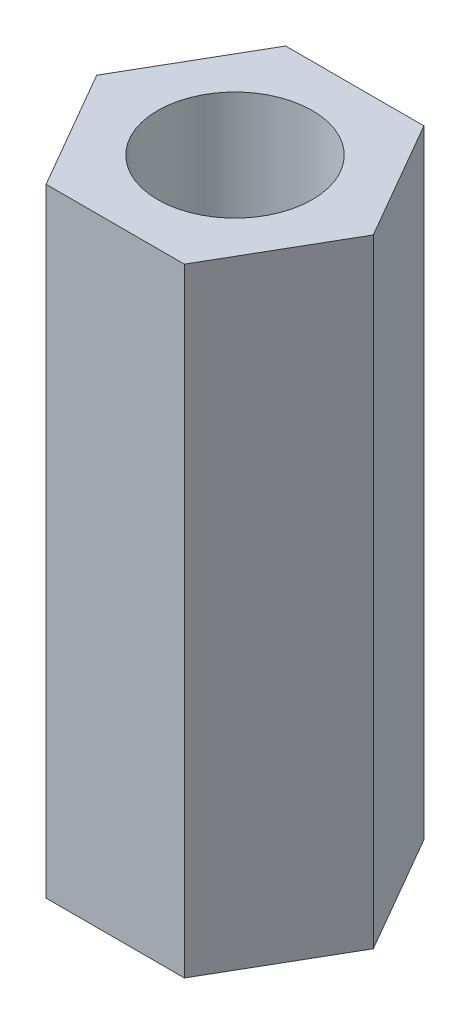
SolidWorks part; units mm, degrees
ref_plane "前视基准面" through (0, 0, 0) normal (0, 0, 1) x (1, 0, 0)
ref_plane "上视基准面" through (0, 0, 0) normal (0, 1, 0) x (1, 0, 0)
ref_plane "右视基准面" through (0, 0, 0) normal (1, 0, 0) x (0, 0, -1)
sketch "草图1" plane through (0, 0, 0) normal (0, 1, 0) x (1, 0, 0)
  line L1 (2.6847, 0) -> (1.3423, 2.325)
  line L2 (1.3423, 2.325) -> (-1.3423, 2.325)
  line L3 (-1.3423, 2.325) -> (-2.6847, 0)
  line L4 (-2.6847, 0) -> (-1.3423, -2.325)
  line L5 (-1.3423, -2.325) -> (1.3423, -2.325)
  line L6 (1.3423, -2.325) -> (2.6847, 0)
  circle A0 centre (0, 0) radius 1.5
  circle A1 centre (0, 0) radius 2.325 construction
  dimension "D2" = 3
  dimension "D1" = 4.65
extrude "凸台-拉伸1" add sketch "草图1" along normal blind 12
cosmetic thread "装饰螺纹线1" parameters "D2"=4
